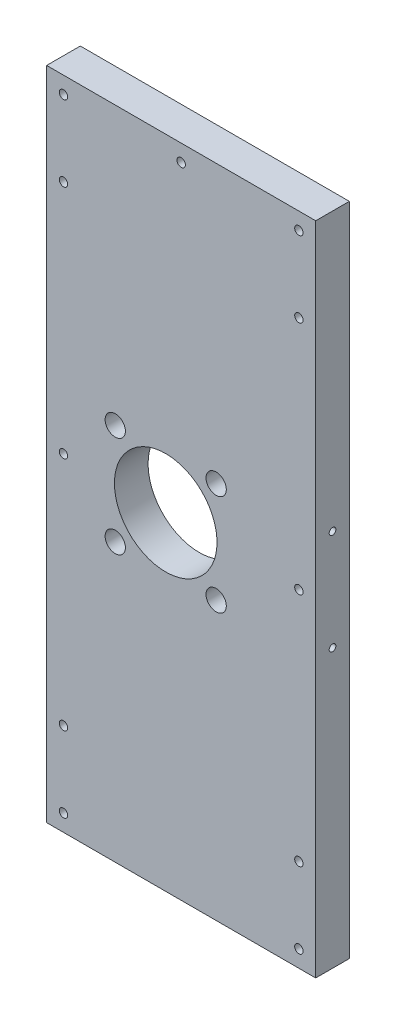
SolidWorks part; units mm, degrees
material "3.0205 (EN-AW 1200)"
ref_plane "Ebene vorne" through (0, 0, 0) normal (0, 0, 1) x (1, 0, 0)
ref_plane "Ebene oben" through (0, 0, 0) normal (0, 1, 0) x (1, 0, 0)
ref_plane "Ebene rechts" through (0, 0, 0) normal (1, 0, 0) x (0, 0, -1)
sketch "Skizze1" plane through (0, 0, 0) normal (0, 0, 1) x (1, 0, 0)
  line L1 (-69.0594, 70.0995) -> (10.9406, 70.0995)
  line L2 (-69.0594, 70.0995) -> (-69.0594, -124.9005)
  line L3 (-69.0594, -124.9005) -> (10.9406, -124.9005)
  line L4 (10.9406, 70.0995) -> (10.9406, -124.9005)
  dimension "D1" = 195
  dimension "D2" = 80
extrude "Aufsatz-Linear austragen1" add sketch "Skizze1" against normal blind 10
sketch "Skizze2" plane through (0, 0, -10) normal (0, 0, -1) x (-1, 0, 0)
  line L0 (33.6594, 70.0995) -> (33.6594, -124.9005) construction
  line L1 (-10.9406, 70.0995) -> (69.0594, 70.0995) construction
  line L2 (69.0594, -124.9005) -> (-10.9406, -124.9005) construction
  line L3 (33.6594, -27.4005) -> (69.0594, -27.4005) construction
  line L4 (69.0594, 70.0995) -> (69.0594, -124.9005) construction
  line L5 (18.6594, -12.4005) -> (48.6594, -12.4005) construction
  line L6 (48.6594, -12.4005) -> (48.6594, -42.4005) construction
  line L7 (48.6594, -42.4005) -> (18.6594, -42.4005) construction
  line L8 (18.6594, -42.4005) -> (18.6594, -12.4005) construction
  line L9 (18.6594, -12.4005) -> (48.6594, -42.4005) construction
  circle A0 centre (18.6594, -12.4005) radius 3.015
  circle A1 centre (48.6594, -12.4005) radius 3.015
  circle A2 centre (18.6594, -42.4005) radius 3.015
  circle A3 centre (48.6594, -42.4005) radius 3.015
  circle A4 centre (33.6594, -27.4005) radius 15.25
  point P22 (33.6594, -27.4005)
  dimension "D1" = 30
  dimension "D3" = 6.03
  dimension "D2" = 30
  dimension "D4" = 35.4
extrude "Schnitt-Linear austragen1" cut sketch "Skizze2" against normal blind 10
sketch "Skizze3" plane through (0, 0, -10) normal (0, 0, -1) x (-1, 0, 0)
  line L0 (-5.9406, 65.0995) -> (64.0594, 65.0995) construction
  line L1 (29.0594, 65.0995) -> (29.0594, 70.0995) construction
  line L2 (-10.9406, 70.0995) -> (69.0594, 70.0995) construction
  line L3 (69.0594, 70.0995) -> (69.0594, -124.9005) construction
  line L4 (-5.9406, -119.9005) -> (64.0594, -119.9005) construction
  line L5 (29.0594, -119.9005) -> (29.0594, -124.9005) construction
  line L6 (69.0594, -124.9005) -> (-10.9406, -124.9005) construction
  line L7 (-5.9406, 42.5995) -> (-5.9406, -27.4005) construction
  line L8 (-5.9406, 42.5995) -> (-5.9406, 65.0995) construction
  line L9 (-5.9406, -27.4005) -> (-5.9406, -97.4005) construction
  line L10 (64.0594, 42.5995) -> (64.0594, 65.0995) construction
  line L11 (64.0594, -97.4005) -> (64.0594, -27.4005) construction
  line L12 (-5.9406, -97.4005) -> (-5.9406, -119.9005) construction
  line L13 (64.0594, -97.4005) -> (64.0594, -119.9005) construction
  line L15 (64.0594, -27.4005) -> (64.0594, 42.5995) construction
  circle A0 centre (29.0594, 65.0995) radius 2.5
  circle A1 centre (-5.9406, 65.0995) radius 2.5
  circle A2 centre (64.0594, 65.0995) radius 2.5
  circle A3 centre (29.0594, -119.9005) radius 2.5
  circle A4 centre (-5.9406, -119.9005) radius 2.5
  circle A5 centre (64.0594, -119.9005) radius 2.5
  circle A6 centre (-5.9406, 42.5995) radius 2.5
  circle A7 centre (-5.9406, -27.4005) radius 2.5
  circle A9 centre (-5.9406, -97.4005) radius 2.5
  circle A10 centre (64.0594, -97.4005) radius 2.5
  circle A12 centre (64.0594, -27.4005) radius 2.5
  circle A13 centre (64.0594, 42.5995) radius 2.5
  dimension "D3" = 5
  dimension "D1" = 5
  dimension "D2" = 5
  dimension "D4" = 70
extrude "Schnitt-Linear austragen2" cut sketch "Skizze3" against normal blind 5
sketch "Skizze6" plane through (0, 0, 0) normal (0, 0, 1) x (1, 0, 0)
  line L0 (-64.0594, 65.0995) -> (-64.0594, 42.5995) construction
  line L2 (-64.0594, 42.5995) -> (-64.0594, -27.4005) construction
  line L3 (-64.0594, -27.4005) -> (-64.0594, -97.4005) construction
  line L4 (-64.0594, -97.4005) -> (-64.0594, -119.9005) construction
  line L5 (-64.0594, 65.0995) -> (5.9406, 65.0995) construction
  line L6 (5.9406, -119.9005) -> (5.9406, -97.4005) construction
  line L7 (5.9406, -97.4005) -> (5.9406, -27.4005) construction
  line L8 (5.9406, -27.4005) -> (5.9406, 42.5995) construction
  line L10 (5.9406, 42.5995) -> (5.9406, 65.0995) construction
  line L11 (-64.0594, -119.9005) -> (5.9406, -119.9005) construction
  line L12 (10.9406, 70.0995) -> (-69.0594, 70.0995) construction
  line L14 (-29.0594, 65.0995) -> (-29.0594, 70.0995) construction
  line L15 (-69.0594, -124.9005) -> (10.9406, -124.9005) construction
  circle A0 centre (-64.0594, 65.0995) radius 1.25
  circle A1 centre (-29.0594, 65.0995) radius 1.25
  circle A2 centre (5.9406, 65.0995) radius 1.25
  circle A3 centre (-64.0594, 42.5995) radius 1.25
  circle A5 centre (-64.0594, -27.4005) radius 1.25
  circle A6 centre (-64.0594, -97.4005) radius 1.25
  circle A7 centre (-64.0594, -119.9005) radius 1.25
  circle A8 centre (5.9406, -119.9005) radius 1.25
  circle A9 centre (5.9406, -97.4005) radius 1.25
  circle A10 centre (5.9406, -27.4005) radius 1.25
  circle A12 centre (5.9406, 42.5995) radius 1.25
  dimension "D2" = 2.5
  dimension "D1" = 5
  dimension "D3" = 5
  dimension "D4" = 70
extrude "Schnitt-Linear austragen4" cut sketch "Skizze6" against normal blind 5
sketch "Skizze7" plane through (-69.0594, 0, 0) normal (-1, 0, 0) x (0, 0, 1)
  line L0 (0, -27.4005) -> (-10, -27.4005) construction
  line L1 (0, 70.0995) -> (0, -124.9005) construction
  line L2 (-10, 70.0995) -> (-10, -124.9005) construction
  line L3 (-5, -27.4005) -> (-5, -42.4005) construction
  line L4 (-5, -27.4005) -> (-5, -12.4005) construction
  circle A0 centre (-5, -12.4005) radius 1
  circle A1 centre (-5, -42.4005) radius 1
  dimension "D1" = 2
  dimension "D2" = 30
extrude "Schnitt-Linear austragen5" cut sketch "Skizze7" against normal blind 20
sketch "Skizze8" plane through (10.9406, 0, 0) normal (1, 0, 0) x (0, 0, -1)
  line L0 (10, -27.4005) -> (0, -27.4005) construction
  line L1 (5, -27.4005) -> (5, -42.4005) construction
  line L2 (5, -27.4005) -> (5, -12.4005) construction
  line L3 (0, -124.9005) -> (0, 70.0995) construction
  line L4 (10, -124.9005) -> (10, 70.0995) construction
  circle A0 centre (5, -12.4005) radius 1
  circle A1 centre (5, -42.4005) radius 1
  dimension "D1" = 2
  dimension "D2" = 30
extrude "Schnitt-Linear austragen6" cut sketch "Skizze8" against normal blind 30
